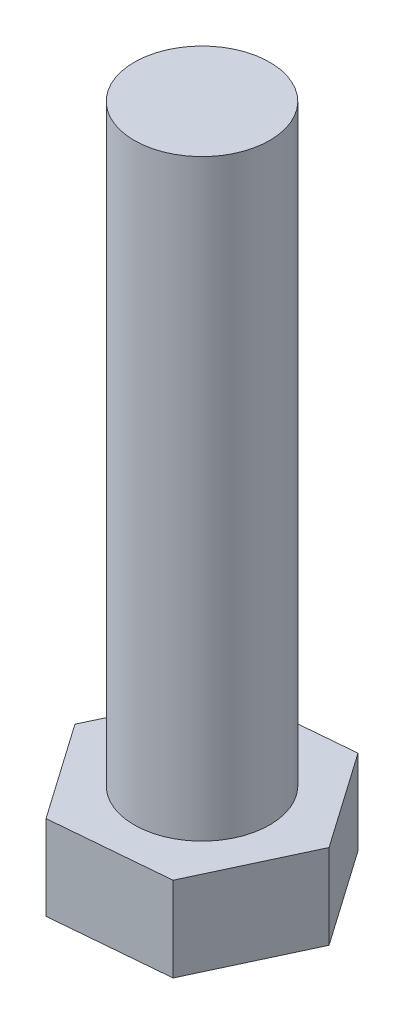
SolidWorks part; units mm, degrees
ref_plane "Front Plane" through (0, 0, 0) normal (0, 0, 1) x (1, 0, 0)
ref_plane "Top Plane" through (0, 0, 0) normal (0, 1, 0) x (1, 0, 0)
ref_plane "Right Plane" through (0, 0, 0) normal (1, 0, 0) x (0, 0, -1)
sketch "Sketch1" plane through (0, 0, 0) normal (0, 1, 0) x (1, 0, 0)
  line L1 (3.9701, -5.6779) -> (6.9022, 0.5993)
  line L2 (6.9022, 0.5993) -> (2.9321, 6.2772)
  line L3 (2.9321, 6.2772) -> (-3.9701, 5.6779)
  line L4 (-3.9701, 5.6779) -> (-6.9022, -0.5993)
  line L5 (-6.9022, -0.5993) -> (-2.9321, -6.2772)
  line L6 (-2.9321, -6.2772) -> (3.9701, -5.6779)
  circle A0 centre (0, 0) radius 6 construction
  dimension "D1" = 12
extrude "Boss-Extrude1" add sketch "Sketch1" along normal blind 5
sketch "Sketch2" plane through (0, 5, 0) normal (0, 1, 0) x (1, 0, 0)
  circle A0 centre (0, 0) radius 4
  dimension "D1" = 8
extrude "Boss-Extrude2" add sketch "Sketch2" along normal blind 35
